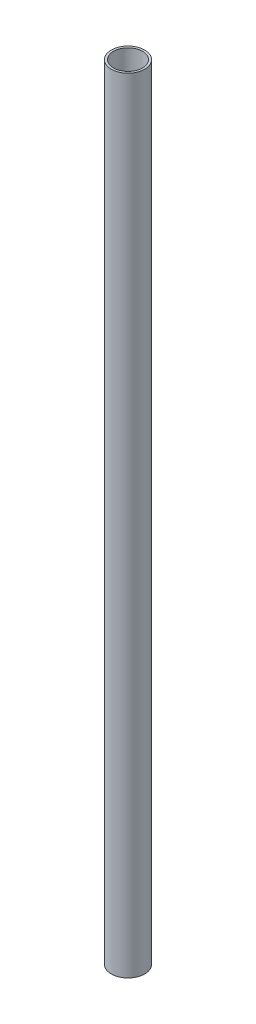
SolidWorks part; units mm, degrees
ref_plane "Front Plane" through (0, 0, 0) normal (0, 0, 1) x (1, 0, 0)
ref_plane "Top Plane" through (0, 0, 0) normal (0, 1, 0) x (1, 0, 0)
ref_plane "Right Plane" through (0, 0, 0) normal (1, 0, 0) x (0, 0, -1)
sketch "Sketch1" plane through (0, 0, 0) normal (0, 1, 0) x (1, 0, 0)
  circle A0 centre (0, 0) radius 9.271
  circle A1 centre (0, 0) radius 10.668
  dimension "D1" = 21.336
  dimension "D2" = 18.542
extrude "Boss-Extrude1" add sketch "Sketch1" along normal blind 501.65
